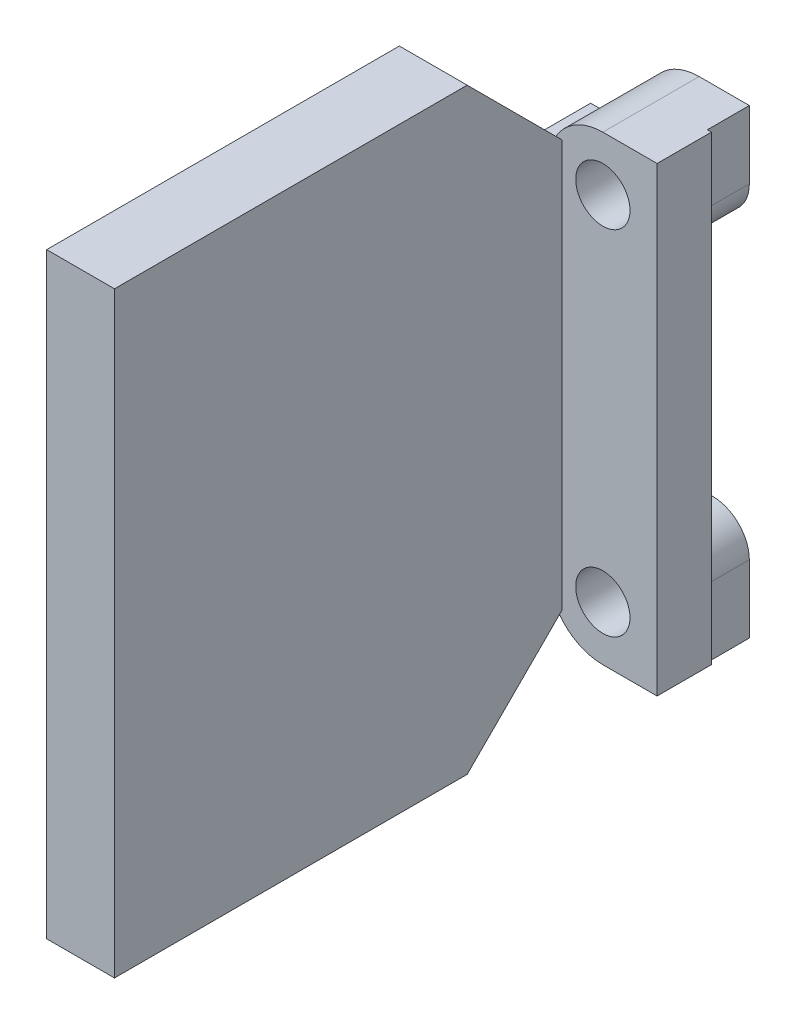
SolidWorks part; units mm, degrees
ref_plane "Top Plane" through (0, 0, 0) normal (0, 0, 1) x (1, 0, 0)
ref_plane "Right Plane" through (0, 0, 0) normal (0, 1, 0) x (1, 0, 0)
ref_plane "Front Plane" through (0, 0, 0) normal (1, 0, 0) x (0, 0, -1)
sketch "Sketch1" plane through (0, 0, 0) normal (0, 0, 1) x (1, 0, 0)
  line L0 (-44, 0) -> (-44, 9)
  line L12 (-36, 17) -> (-32, 17)
  line L15 (-32, 0) -> (-32, 17)
  line L18 (-44, 0) -> (-32, 0)
  arc A4 (-36, 17) -> (-40, 13) centre (-36, 13) ccw
  arc A5 (-44, 9) -> (-40, 13) centre (-44, 13) ccw
  circle A9 centre (-36, 13) radius 2
extrude "Boss-Extrude1" add sketch "Sketch1" along normal blind 4
sketch "Sketch2" plane through (0, 0, 0) normal (0, 0, -1) x (-1, 0, 0)
  line L0 (32, 12) -> (32, 24.9289) construction
  line L1 (35, 9) -> (44, 9) construction
  line L2 (32, 12) -> (32, 24.9289) construction
  line L3 (35, 9) -> (44, 9) construction
  line L4 (35, 9.3) -> (42.4801, 9.3)
  line L5 (32.3, 12) -> (32.3, 17)
  line L6 (36, 17) -> (32.3, 17)
  line L7 (32.3, 12) -> (32.3, 24.9289) construction
  line L8 (35, 9.3) -> (44, 9.3) construction
  line L9 (32, 17) -> (36, 17) construction
  arc A0 (32, 12) -> (35, 9) centre (35, 12) ccw construction
  arc A1 (32, 12) -> (35, 9) centre (35, 12) ccw construction
  arc A2 (32.3, 12) -> (35, 9.3) centre (35, 12) ccw
  arc A3 (40, 13) -> (43.995, 9) centre (44, 13) ccw construction
  arc A4 (40, 13) -> (36, 17) centre (36, 13) ccw construction
  arc A6 (40, 13) -> (42.4801, 9.3) centre (44, 13) ccw
  arc A7 (40, 13) -> (36, 17) centre (36, 13) ccw
  circle A9 centre (36, 13) radius 2 construction
  circle A10 centre (36, 13) radius 2
  dimension "D1" = 0.3
extrude "Boss-Extrude2" add sketch "Sketch2" along normal offset from surface (3.1 mm away) 0.1
sketch "Sketch4" plane through (-44, -0.0245, 0) normal (1, 0, 0) x (0, 0, 1)
  line L1 (0.3, -11.3245) -> (11, -22.0245)
  line L2 (11, -22.0245) -> (37, -22.0245)
  line L3 (37, -22.0245) -> (37, -0.0245)
  line L4 (37, -0.0245) -> (0, -0.0245)
  line L6 (0.3, -11.3245) -> (11, -11.3245) construction
  line L7 (11, -11.3245) -> (11, -22.0245) construction
  line L9 (-3, -9.0245) -> (-3, 8.9755) construction
  line L10 (0, -9.3245) -> (0, -0.0245)
  line L11 (0, -9.3245) -> (-3.1, -9.3245)
  line L12 (-3.1, -9.3245) -> (-3.1, -11.3245)
  line L13 (-3.1, -11.3245) -> (0.3, -11.3245)
  line L14 (-3.1, -9.3245) -> (0, -9.3245) construction
  dimension "D1" = 40
  dimension "D2" = 26
  dimension "D3" = 22
  dimension "D4" = 2
extrude "Boss-Extrude3" add sketch "Sketch4" along normal blind 5
mirror "Mirror1" about plane through (-44, 0, 4) normal (0, 1, 0) of bodies 104
